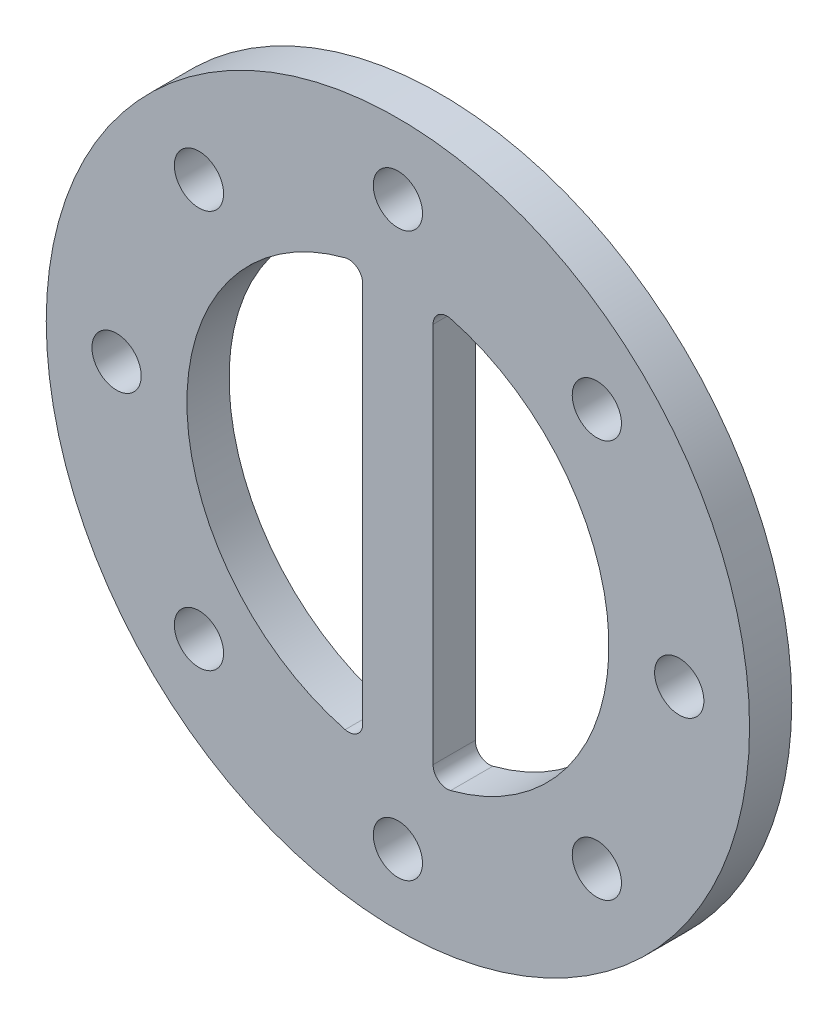
SolidWorks part; units mm, degrees
ref_plane "Front Plane" through (0, 0, 0) normal (0, 0, 1) x (1, 0, 0)
ref_plane "Top Plane" through (0, 0, 0) normal (0, 1, 0) x (1, 0, 0)
ref_plane "Right Plane" through (0, 0, 0) normal (1, 0, 0) x (0, 0, -1)
sketch "Sketch1" plane through (0, 0, 0) normal (0, 0, 1) x (1, 0, 0)
  circle A0 centre (0, 0) radius 25
  dimension "D1" = 50
extrude "Boss-Extrude1" add sketch "Sketch1" along normal blind 3
sketch "Sketch2" plane through (0, 0, 3) normal (0, 0, 1) x (1, 0, 0)
  line L0 (0, 20) -> (0, 0) construction
  circle A0 centre (0, 20) radius 1.75
  dimension "D2" = 3.5
  dimension "D1" = 20
extrude "Cut-Extrude1" cut sketch "Sketch2" against normal blind 3
pattern_circular "CirPattern1" count 8 over 360 about axis through (0, 0, 0) along (0, 0, 1) of "Cut-Extrude1"
sketch "Sketch3" plane through (0, 0, 3) normal (0, 0, 1) x (1, 0, 0)
  line L0 (-2.5, 14.7902) -> (-2.5, -14.7902)
  line L2 (2.5, 14.7902) -> (2.5, -14.7902)
  arc A0 (-2.5, 14.7902) -> (-2.5, -14.7902) centre (0, 0) ccw
  arc A1 (2.5, -14.7902) -> (2.5, 14.7902) centre (0, 0) ccw
  dimension "D1" = 30
  dimension "D2" = 5
extrude "Cut-Extrude2" cut sketch "Sketch3" against normal blind 10
fillet "Fillet1" radius 1 4 edges at (2.5, -14.7902, 1.5) (2.5, 14.7902, 1.5) (-2.5, -14.7902, 1.5) (-2.5, 14.7902, 1.5)
